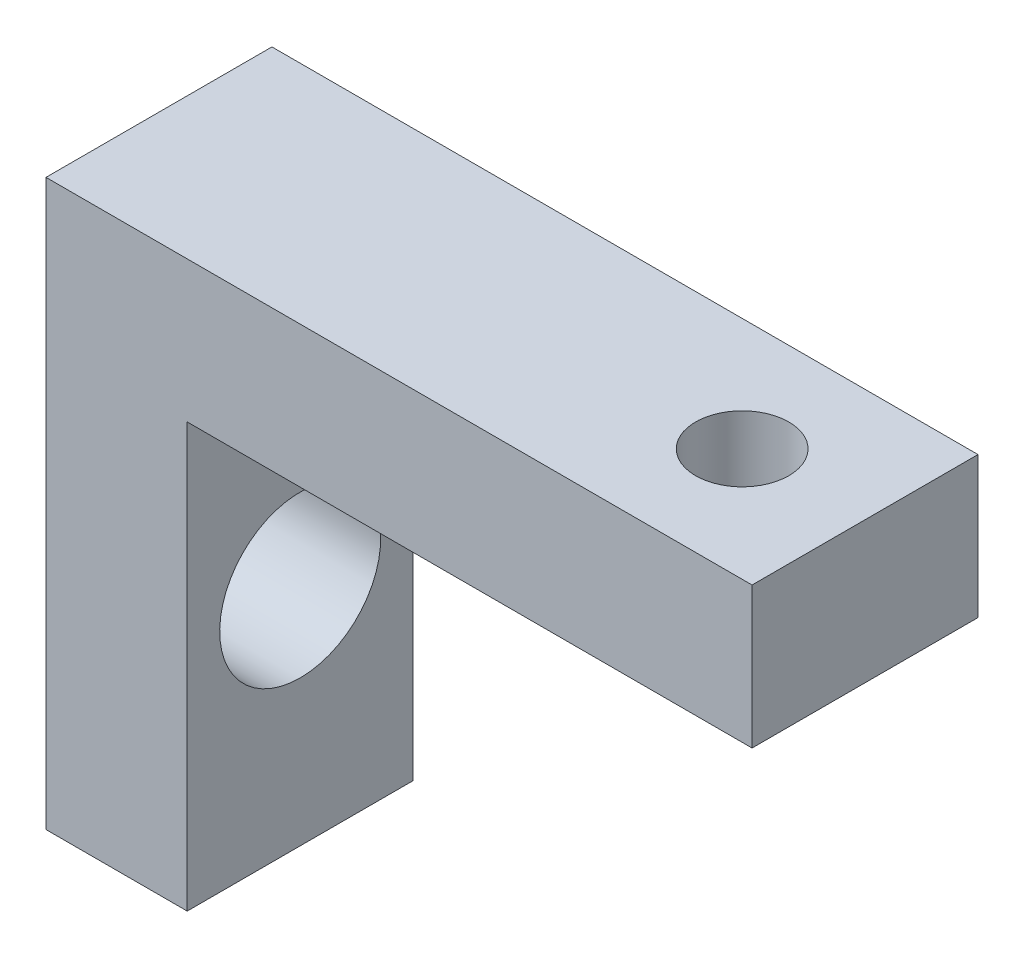
SolidWorks part; units mm, degrees
ref_plane "前视基准面" through (0, 0, 0) normal (0, 0, 1) x (1, 0, 0)
ref_plane "上视基准面" through (0, 0, 0) normal (0, 1, 0) x (1, 0, 0)
ref_plane "右视基准面" through (0, 0, 0) normal (1, 0, 0) x (0, 0, -1)
sketch "草图1" plane through (0, 0, 0) normal (0, 0, 1) x (1, 0, 0)
  line L0 (0, 0) -> (0, -15)
  line L1 (0, -15) -> (-5, -15)
  line L2 (-5, -15) -> (-5, 5)
  line L3 (-5, 5) -> (20, 5)
  line L4 (20, 5) -> (20, 0)
  line L5 (20, 0) -> (0, 0)
  dimension "D1" = 25
  dimension "D2" = 20
  dimension "D3" = 5
  dimension "D4" = 5
extrude "凸台-拉伸1" add sketch "草图1" along normal blind 8
sketch "草图2" plane through (0, 0, 0) normal (0, -1, 0) x (1, 0, 0)
  line L1 (-5, 8) -> (-5, 0) construction
  circle A0 centre (15.65, 4) radius 1.65
  dimension "D1" = 3.3
  dimension "D2" = 20.65
extrude "切除-拉伸1" cut sketch "草图2" against normal blind 8
sketch "草图3" plane through (-5, 0, 0) normal (-1, 0, 0) x (0, 0, 1)
  line L0 (8, 5) -> (0, 5) construction
  circle A0 centre (4, -7) radius 2.85
  dimension "D2" = 5.7
  dimension "D1" = 12
extrude "切除-拉伸2" cut sketch "草图3" against normal blind 8
